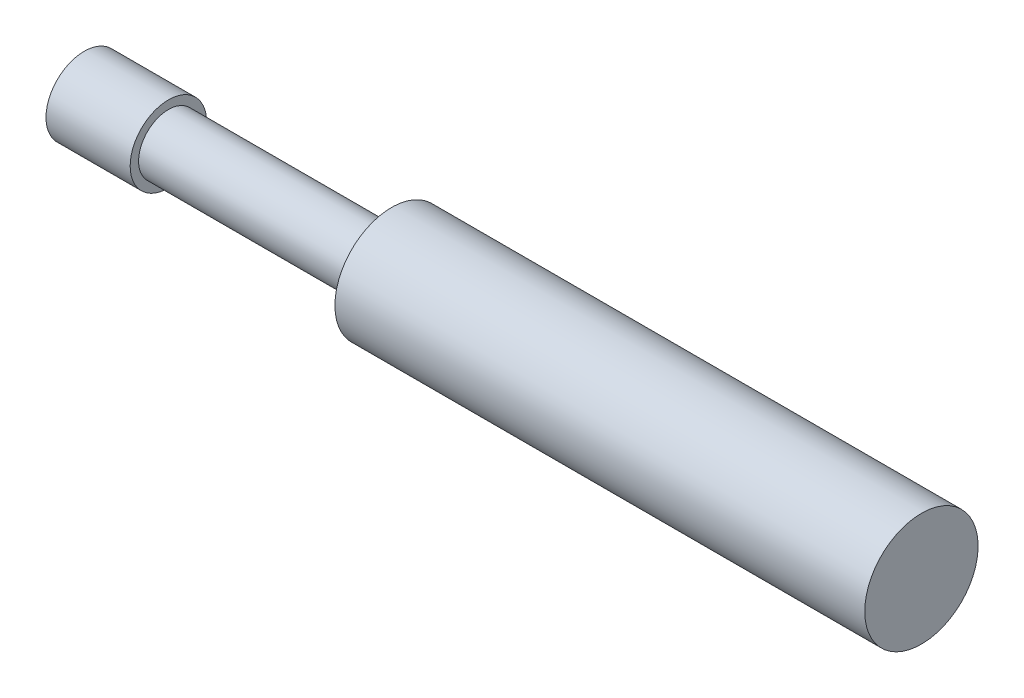
SolidWorks part; units mm, degrees
material "1023 Carbon Steel Sheet (SS)"
ref_plane "Front Plane" through (0, 0, 0) normal (0, 0, 1) x (1, 0, 0)
ref_plane "Top Plane" through (0, 0, 0) normal (0, 1, 0) x (1, 0, 0)
ref_plane "Right Plane" through (0, 0, 0) normal (1, 0, 0) x (0, 0, -1)
sketch "Sketch2" plane through (0, 0, 0) normal (0, 0, 1) x (1, 0, 0)
  line L0 (0, 0) -> (-112.268, 0)
  line L1 (-112.268, 0) -> (-112.268, 13.97)
  line L2 (0, 10.8956) -> (0, 20.701)
  line L3 (-112.268, 13.97) -> (-81.5237, 13.97)
  line L4 (-81.5237, 13.97) -> (-81.5237, 10.8956)
  line L5 (-81.5237, 10.8956) -> (0, 10.8956)
  line L6 (0, 20.701) -> (193.548, 20.701)
  line L7 (0, 0) -> (193.548, 0)
  line L8 (193.548, 20.701) -> (193.548, 0)
  dimension "D1" = 20.701
  dimension "D2" = 13.97
  dimension "D3" = 112.268
  dimension "D4" = 305.816
revolve "Revolve1" add sketch "Sketch2" angle 360 about L7
